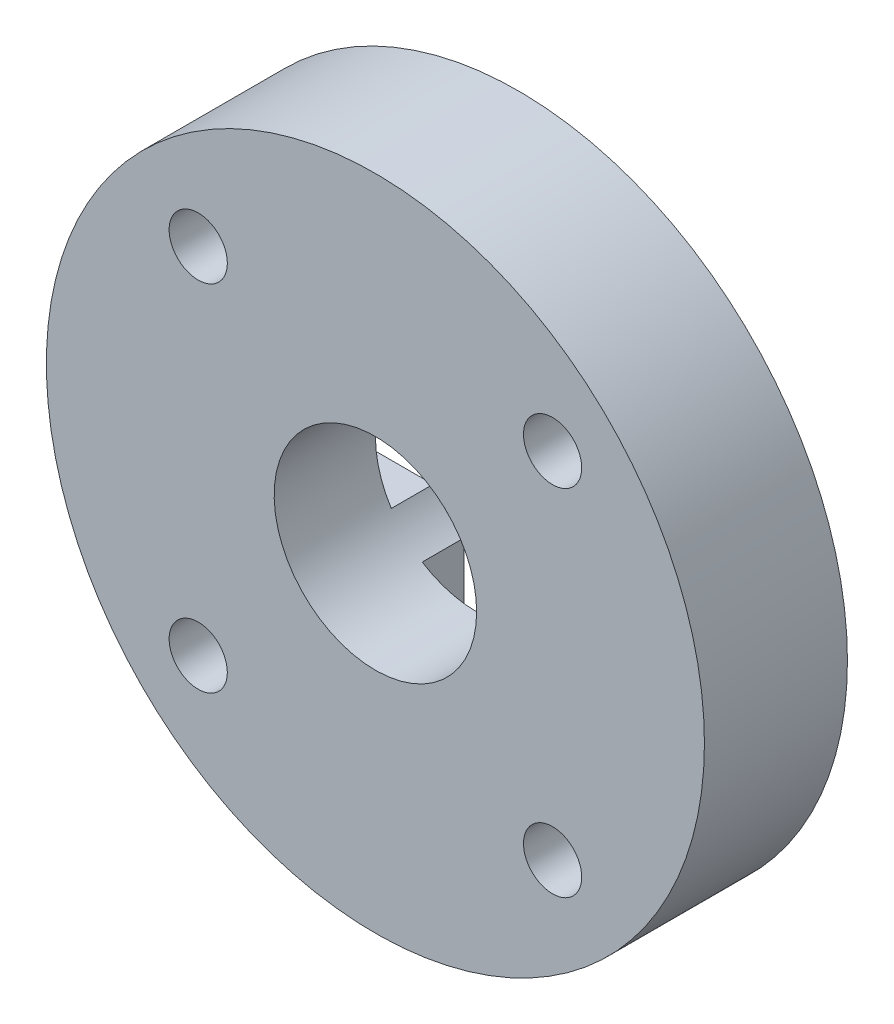
SolidWorks part; units mm, degrees
ref_plane "Front Plane" through (0, 0, 0) normal (0, 0, 1) x (1, 0, 0)
ref_plane "Top Plane" through (0, 0, 0) normal (0, 1, 0) x (1, 0, 0)
ref_plane "Right Plane" through (0, 0, 0) normal (1, 0, 0) x (0, 0, -1)
sketch "Trial_load_plate_profile" plane through (0, 0, 0) normal (0, 0, 1) x (1, 0, 0)
  circle A0 centre (0, 0) radius 13
  circle A1 centre (0, 0) radius 4
  dimension "D1" = 26
  dimension "D2" = 8
extrude "Trial_load_plate" add sketch "Trial_load_plate_profile" along normal blind 4
sketch "Captured_horn_key_boss_profile" plane through (0, 0, 0) normal (0, 0, 1) x (1, 0, 0)
  circle A0 centre (0, 0) radius 13
  dimension "D1" = 26
extrude "Captured_horn_key_boss" add sketch "Captured_horn_key_boss_profile" along normal blind 1.65 from offset 1.65
sketch "Stock_horn_pocket_Hub" plane through (0, 0, 0) normal (0, 0, 1) x (1, 0, 0)
  circle A0 centre (0, 0) radius 3.6
  dimension "D1" = 7.2
extrude "Key_pocket_Hub" cut sketch "Stock_horn_pocket_Hub" along normal blind 1.65 from offset 1.65
sketch "Stock_horn_pocket_Horizontal" plane through (0, 0, 0) normal (0, 0, 1) x (1, 0, 0)
  line L1 (-8.15, -2.15) -> (8.15, -2.15)
  line L2 (-8.15, -2.15) -> (-8.15, 2.15)
  line L3 (-8.15, 2.15) -> (8.15, 2.15)
  line L4 (8.15, -2.15) -> (8.15, 2.15)
  dimension "D1" = 16.3
  dimension "D2" = 4.3
extrude "Key_pocket_Horizontal" cut sketch "Stock_horn_pocket_Horizontal" along normal blind 1.65 from offset 1.65
sketch "Stock_horn_pocket_Vertical" plane through (0, 0, 0) normal (0, 0, 1) x (1, 0, 0)
  line L1 (-2.15, -8.15) -> (2.15, -8.15)
  line L2 (-2.15, -8.15) -> (-2.15, 8.15)
  line L3 (-2.15, 8.15) -> (2.15, 8.15)
  line L4 (2.15, -8.15) -> (2.15, 8.15)
  dimension "D1" = 4.3
  dimension "D2" = 16.3
extrude "Key_pocket_Vertical" cut sketch "Stock_horn_pocket_Vertical" along normal blind 1.65 from offset 1.65
sketch "Stock_horn_pocket_Rounded_tips" plane through (0, 0, 0) normal (0, 0, 1) x (1, 0, 0)
  circle A0 centre (8.15, 0) radius 2.15
  circle A1 centre (-8.15, 0) radius 2.15
  circle A2 centre (0, 8.15) radius 2.15
  circle A3 centre (0, -8.15) radius 2.15
  dimension "D1" = 4.3
  dimension "D2" = 4.3
  dimension "D3" = 4.3
  dimension "D4" = 4.3
extrude "Key_pocket_Rounded_tips" cut sketch "Stock_horn_pocket_Rounded_tips" along normal blind 1.65 from offset 1.65
sketch "Unmodified_horn_capture_M2_profile" plane through (0, 0, 0) normal (0, 0, 1) x (1, 0, 0)
  circle A0 centre (7, 7) radius 1.15
  circle A1 centre (-7, 7) radius 1.15
  circle A2 centre (-7, -7) radius 1.15
  circle A3 centre (7, -7) radius 1.15
  dimension "D1" = 2.3
  dimension "D2" = 2.3
  dimension "D3" = 2.3
  dimension "D4" = 2.3
extrude "Unmodified_horn_capture_M2" cut sketch "Unmodified_horn_capture_M2_profile" along normal through all from offset 50
sketch "Horn_center_hub_clearance" plane through (0, 0, 0) normal (0, 0, 1) x (1, 0, 0)
  circle A0 centre (0, 0) radius 4
  dimension "D1" = 8
extrude "Hub_clearance_in_key_boss_only" cut sketch "Horn_center_hub_clearance" along normal blind 1.65 from offset 1.65
